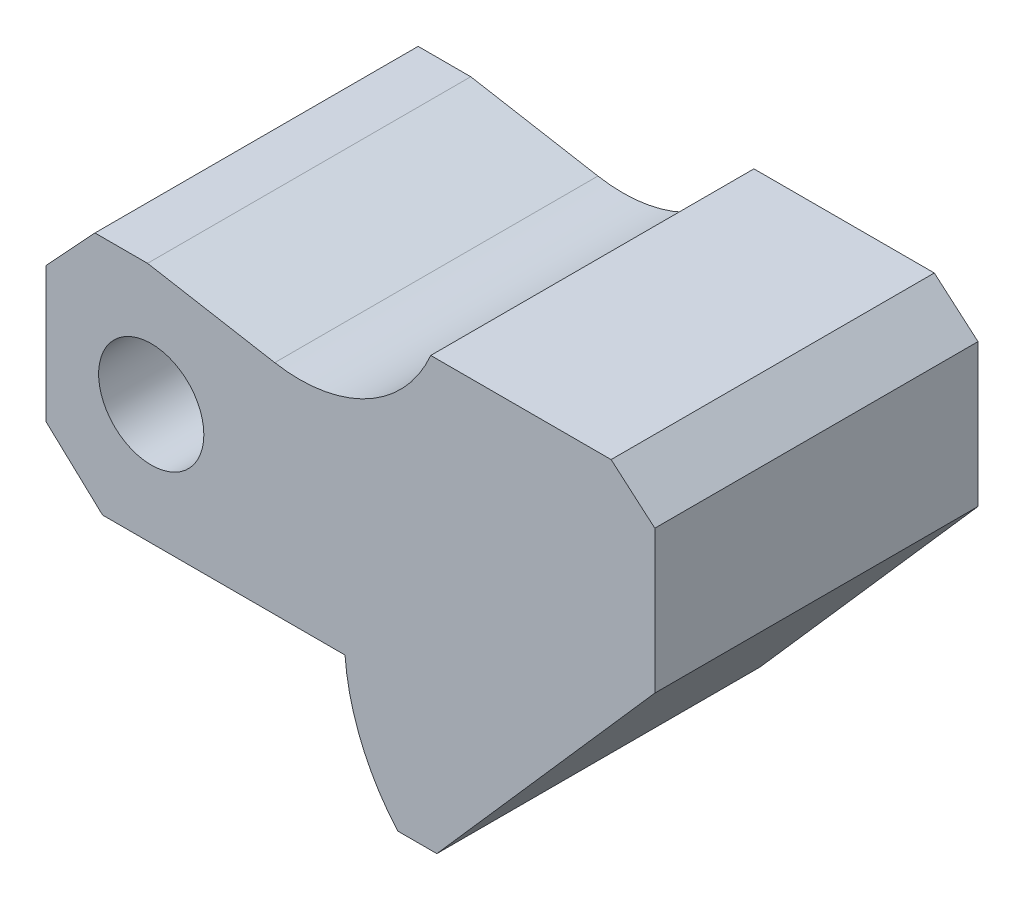
SolidWorks part; units mm, degrees
material "AISI 1020 Steel, Cold Rolled"
ref_plane "Front Plane" through (0, 0, 0) normal (0, 0, 1) x (1, 0, 0)
ref_plane "Top Plane" through (0, 0, 0) normal (0, 1, 0) x (1, 0, 0)
ref_plane "Right Plane" through (0, 0, 0) normal (1, 0, 0) x (0, 0, -1)
other "Center of Mass"
sketch "Sketch3" plane through (0, 0, 0) normal (0, 0, 1) x (1, 0, 0)
  line L0 (-26.2905, 12.8557) -> (-26.2905, -5.1443)
  line L1 (-12.2905, 3.8557) -> (-40.2905, 3.8557) construction
  line L2 (-26.2905, 12.8557) -> (-19.7782, 19.8557)
  line L3 (-12.7782, 19.8557) -> (4.1416, 16.8723)
  line L4 (-19.7782, 19.8557) -> (-12.7782, 19.8557)
  line L5 (54.7095, 23.0808) -> (54.7095, 4.0808)
  line L6 (-26.2905, -5.1443) -> (-18.7663, -12.1443)
  line L7 (54.7095, 23.0808) -> (48.8968, 28.0808)
  line L8 (48.8968, 28.0808) -> (24.8968, 28.0808)
  line L9 (-26.2905, -5.1443) -> (-26.2905, -12.1443) construction
  line L10 (-26.2905, -5.1443) -> (-18.7663, -12.1443)
  line L11 (54.7095, 4.0808) -> (54.7095, -28.9192) construction
  line L12 (54.7095, -28.9192) -> (25.7095, -28.9192) construction
  line L13 (54.7095, 4.0808) -> (25.7095, -28.9192)
  line L14 (42.4065, -28.9192) -> (42.4065, -9.9192) construction
  line L15 (25.7095, -28.9192) -> (20.4976, -28.9192)
  line L16 (-18.7663, -12.1443) -> (13.4919, -12.1443)
  circle A0 centre (-12.2905, 3.8557) radius 7
  arc A1 (4.1416, 16.8723) -> (24.8968, 28.0808) centre (7.4409, 35.5836) ccw
  arc A2 (13.4919, -12.1443) -> (20.4976, -28.9192) centre (42.4065, -9.9192) ccw
  point P4 (-26.2905, 3.8557)
  dimension "D1" = 18
  dimension "D3" = 7
  dimension "D7" = 29
  dimension "D9" = 19
  dimension "D2" = 7
  dimension "D4" = 19
  dimension "D5" = 33
  dimension "D6" = 29
  dimension "D8" = 24
  dimension "D10" = 81
  dimension "D11" = 7
  dimension "D12" = 5
  dimension "D13" = 10
extrude "Boss-Extrude1" add sketch "Sketch3" along normal blind 43 contours L16 A2 L15 L13 L5 L7 L8 A1 L3 L4 L2 L0 L6 A0
